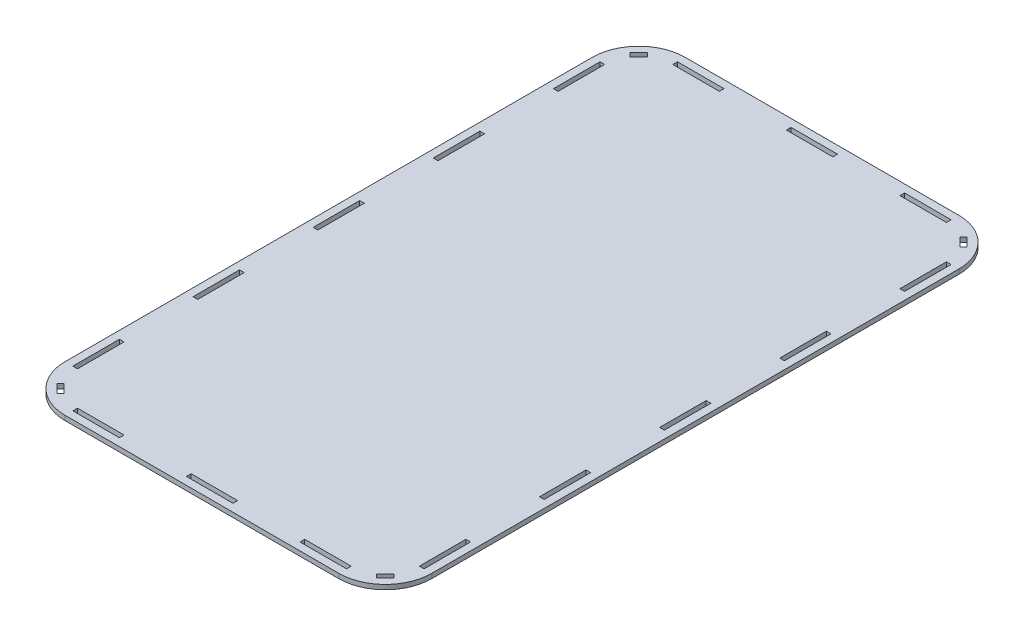
SolidWorks part; units mm, degrees
ref_plane "Front Plane" through (0, 0, 0) normal (0, 0, 1) x (1, 0, 0)
ref_plane "Top Plane" through (0, 0, 0) normal (0, 1, 0) x (1, 0, 0)
ref_plane "Right Plane" through (0, 0, 0) normal (1, 0, 0) x (0, 0, -1)
sketch "Sketch1" plane through (0, 0, 0) normal (0, 1, 0) x (1, 0, 0)
  line L1 (-118.25, -200) -> (118.25, -200)
  line L2 (-118.25, -200) -> (-118.25, 200)
  line L3 (-118.25, 200) -> (118.25, 200)
  line L4 (118.25, -200) -> (118.25, 200)
  line L5 (-118.25, -200) -> (118.25, 200) construction
  line L6 (-118.25, 200) -> (118.25, -200) construction
  point P0 (0, 0)
  dimension "D1" = 400
  dimension "D2" = 236.5
extrude "Boss-Extrude1" add sketch "Sketch1" along normal mid plane 3
fillet "Fillet1" radius 30 4 edges at (-118.25, 0, 200) (-118.25, 0, -200) (118.25, 0, -200) (118.25, 0, 200)
sketch "Sketch2" plane through (0, 1.5, 0) normal (0, 1, 0) x (1, 0, 0)
  line L0 (-118.25, 170) -> (-118.25, -170) construction
  line L1 (-113.25, -170) -> (-110.25, -170)
  line L2 (-113.25, -170) -> (-113.25, -140)
  line L3 (-113.25, -140) -> (-110.25, -140)
  line L4 (-110.25, -170) -> (-110.25, -140)
  line L5 (-113.25, -92.5) -> (-113.25, -62.5)
  line L6 (-113.25, -92.5) -> (-110.25, -92.5)
  line L7 (-110.25, -92.5) -> (-110.25, -62.5)
  line L8 (-113.25, -62.5) -> (-110.25, -62.5)
  line L9 (-113.25, -15) -> (-113.25, 15)
  line L10 (-113.25, -15) -> (-110.25, -15)
  line L11 (-110.25, -15) -> (-110.25, 15)
  line L12 (-113.25, 15) -> (-110.25, 15)
  line L13 (-113.25, 62.5) -> (-113.25, 92.5)
  line L14 (-113.25, 62.5) -> (-110.25, 62.5)
  line L15 (-110.25, 62.5) -> (-110.25, 92.5)
  line L16 (-113.25, 92.5) -> (-110.25, 92.5)
  line L17 (-113.25, 140) -> (-113.25, 170)
  line L18 (-113.25, 140) -> (-110.25, 140)
  line L19 (-110.25, 140) -> (-110.25, 170)
  line L20 (-113.25, 170) -> (-110.25, 170)
  dimension "D1" = 3
  dimension "D2" = 5
  dimension "D3" = 30
  dimension "D4" = 5
extrude "Cut-Extrude1" cut sketch "Sketch2" against normal through all
sketch "Sketch3" plane through (0, 1.5, 0) normal (0, 1, 0) x (1, 0, 0)
  line L0 (-110.25, 170) -> (-113.25, 170) construction
  line L1 (-88.25, 195) -> (-58.25, 195)
  line L2 (-88.25, 195) -> (-88.25, 192)
  line L3 (-88.25, 192) -> (-58.25, 192)
  line L4 (-58.25, 195) -> (-58.25, 192)
  line L5 (-110.25, 140) -> (-110.25, 170) construction
  line L6 (-113.25, 170) -> (-118.25, 170) construction
  line L7 (-88.25, 195) -> (-88.25, 200) construction
  line L8 (-15, 195) -> (-15, 192)
  line L9 (-15, 195) -> (15, 195)
  line L10 (15, 195) -> (15, 192)
  line L11 (-15, 192) -> (15, 192)
  line L12 (58.25, 195) -> (58.25, 192)
  line L13 (58.25, 195) -> (88.25, 195)
  line L14 (88.25, 195) -> (88.25, 192)
  line L15 (58.25, 192) -> (88.25, 192)
  dimension "D1" = 3
extrude "Cut-Extrude2" cut sketch "Sketch3" against normal through all
mirror "Mirror1" about plane through (0, 0, 0) normal (0, 0, 1) of "Cut-Extrude2"
mirror "Mirror2" about plane through (0, 0, 0) normal (1, 0, 0) of "Cut-Extrude1"
sketch "Sketch4" plane through (0, 1.5, 0) normal (0, 1, 0) x (1, 0, 0)
  line L0 (-103.8063, 185.5563) -> (-105.9277, 187.6777) construction
  line L1 (-108.7561, 184.8492) -> (-103.0992, 190.5061)
  line L2 (-103.0992, 190.5061) -> (-100.7186, 188.1255)
  line L3 (-100.7186, 188.1255) -> (-106.3755, 182.4686)
  line L4 (-106.3755, 182.4686) -> (-108.7561, 184.8492)
  line L5 (0, 200) -> (0, -200) construction
  line L6 (88.25, 200) -> (-88.25, 200) construction
  line L7 (-88.25, -200) -> (88.25, -200) construction
  line L8 (118.25, 0) -> (-118.25, 0) construction
  line L9 (118.25, -170) -> (118.25, 170) construction
  line L10 (-118.25, 170) -> (-118.25, -170) construction
  line L11 (100.7186, 188.1255) -> (106.3755, 182.4686)
  line L12 (103.0992, 190.5061) -> (100.7186, 188.1255)
  line L13 (108.7561, 184.8492) -> (103.0992, 190.5061)
  line L14 (106.3755, 182.4686) -> (108.7561, 184.8492)
  line L15 (103.0992, -190.5061) -> (100.7186, -188.1255)
  line L16 (108.7561, -184.8492) -> (103.0992, -190.5061)
  line L17 (106.3755, -182.4686) -> (108.7561, -184.8492)
  line L18 (100.7186, -188.1255) -> (106.3755, -182.4686)
  line L19 (-100.7186, -188.1255) -> (-106.3755, -182.4686)
  line L20 (-103.0992, -190.5061) -> (-100.7186, -188.1255)
  line L21 (-108.7561, -184.8492) -> (-103.0992, -190.5061)
  line L22 (-106.3755, -182.4686) -> (-108.7561, -184.8492)
  arc A0 (-88.25, 192) -> (-110.25, 170) centre (-88.25, 170) ccw construction
  arc A1 (-88.25, 195) -> (-113.25, 170) centre (-88.25, 170) ccw construction
  arc A2 (-88.25, 200) -> (-118.25, 170) centre (-88.25, 170) ccw construction
  point P17 (-105.9277, 187.6777)
  dimension "D1" = 8
extrude "Cut-Extrude3" cut sketch "Sketch4" against normal through all
